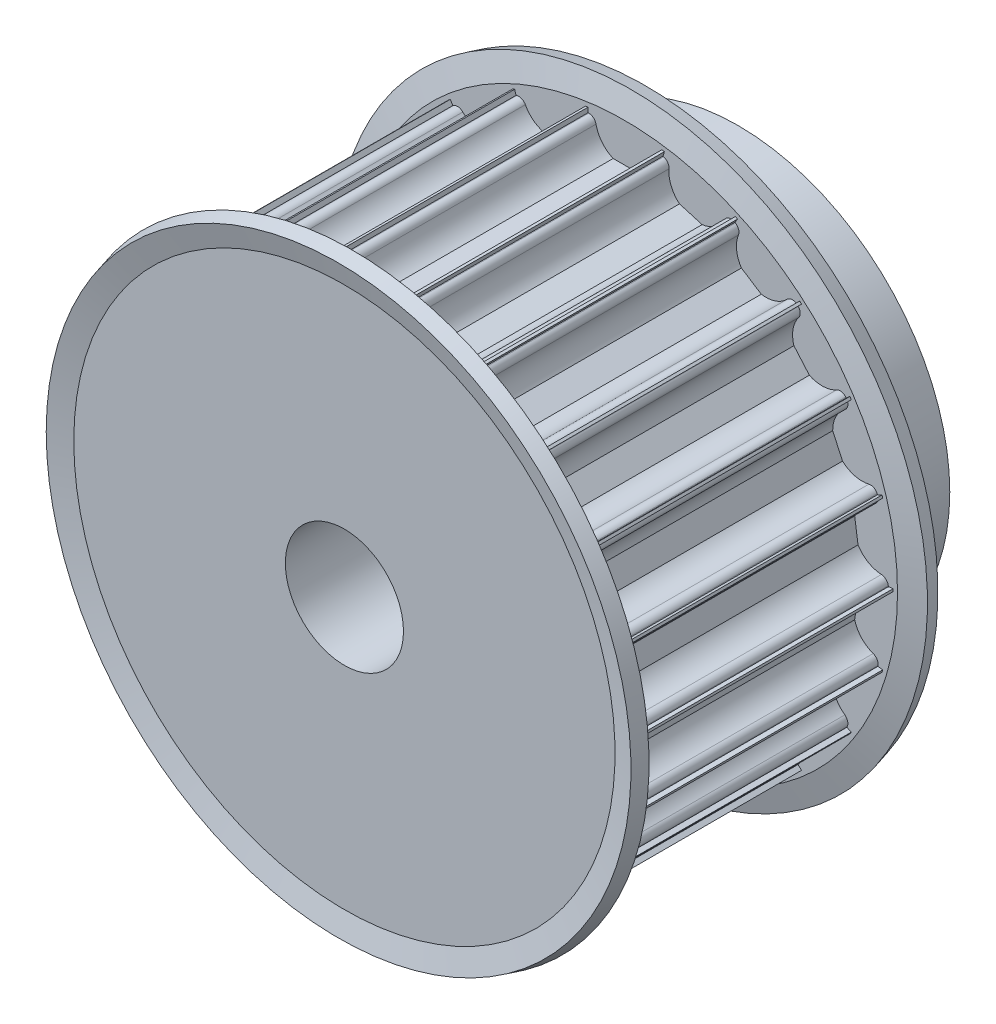
SolidWorks part; units mm, degrees
ref_plane "Front Plane" through (0, 0, 0) normal (0, 0, 1) x (1, 0, 0)
ref_plane "Top Plane" through (0, 0, 0) normal (0, 1, 0) x (1, 0, 0)
ref_plane "Right Plane" through (0, 0, 0) normal (1, 0, 0) x (0, 0, -1)
sketch "Sketch2" plane through (0, 0, 0) normal (1, 0, 0) x (0, 0, -1)
  line L0 (0, 0) -> (89.4717, 0) construction
  line L1 (0, 6) -> (0, 27.25)
  line L2 (0, 27.25) -> (30, 27.25)
  line L3 (30, 27.25) -> (30, 21.5)
  line L4 (30, 21.5) -> (40, 21.5)
  line L5 (40, 21.5) -> (40, 6)
  line L6 (40, 6) -> (0, 6)
  dimension "D1" = 27.25
  dimension "D2" = 6
  dimension "D3" = 30
  dimension "D4" = 10
  dimension "D5" = 15.5
revolve "Revolve1" add sketch "Sketch2" angle 360 about L0
sketch "Sketch3" plane through (0, 0, 0) normal (0, 0, 1) x (1, 0, 0)
  line L0 (-3.6742, 26.5) -> (-3.75, 26.5)
  line L1 (-3.75, 26.5) -> (-3.75, 28.5)
  line L2 (-3.75, 28.5) -> (3.75, 28.5)
  line L3 (3.75, 28.5) -> (3.75, 26.5)
  line L4 (3.75, 26.5) -> (3.6742, 26.5)
  line L5 (-1.199, 23.75) -> (1.199, 23.75)
  arc A0 (2.9394, 25.9) -> (1.199, 23.75) centre (0, 26.5) cw
  arc A1 (2.9394, 25.9) -> (3.6742, 26.5) centre (3.6742, 25.75) cw
  arc A2 (-2.9394, 25.9) -> (-3.6742, 26.5) centre (-3.6742, 25.75) ccw
  arc A3 (-1.199, 23.75) -> (-2.9394, 25.9) centre (0, 26.5) cw
  point P9 (0, 28.5)
  dimension "D2" = 3
  dimension "D6" = 0.75
  dimension "D1" = 26.5
  dimension "D3" = 2
  dimension "D4" = 7.5
  dimension "D5" = 2.75
extrude "Cut-Extrude1" cut sketch "Sketch3" against normal up to next
pattern_circular "CirPattern1" count 22 over 360 about axis through (0, 0, 0) along (0, 0, 1) of "Cut-Extrude1"
sketch "Sketch4" plane through (0, 0, 0) normal (1, 0, 0) x (0, 0, -1)
  line L0 (15, 26.9539) -> (15, 0.1345) construction
  line L1 (30, 26.9539) -> (0, 26.9539) construction
  line L2 (30, 0.1345) -> (0, 0.1345) construction
  line L3 (30, 21.5) -> (30, 27.4925)
  line L4 (30, 27.4925) -> (30.592, 29.7018)
  line L5 (30.592, 29.7018) -> (29.1431, 30.09)
  line L6 (29.1431, 30.09) -> (28.5, 27.69)
  line L7 (28.5, 27.69) -> (28.5, 21.5)
  line L8 (28.5, 21.5) -> (30, 21.5)
  line L9 (1.5, 21.5) -> (0, 21.5)
  line L10 (1.5, 27.69) -> (1.5, 21.5)
  line L11 (0, 21.5) -> (0, 27.4925)
  line L12 (-0.592, 29.7018) -> (0.8569, 30.09)
  line L13 (0, 27.4925) -> (-0.592, 29.7018)
  line L14 (0.8569, 30.09) -> (1.5, 27.69)
  line L15 (0, 0) -> (-34.5262, 0) construction
  dimension "D1" = 1.5
  dimension "D2" = 6.19
  dimension "D3" = 2.4
  dimension "D4" = 15
revolve "Revolve2" add sketch "Sketch4" angle 360 about L15
